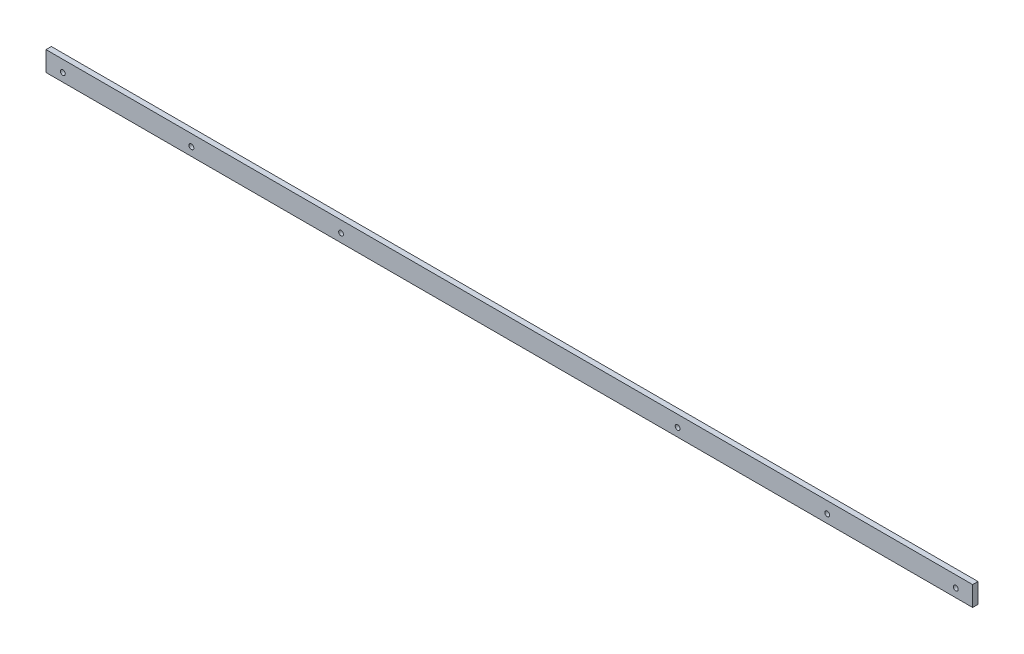
SolidWorks part; units mm, degrees
ref_plane "Front Plane" through (0, 0, 0) normal (0, 0, 1) x (1, 0, 0)
ref_plane "Top Plane" through (0, 0, 0) normal (0, 1, 0) x (1, 0, 0)
ref_plane "Right Plane" through (0, 0, 0) normal (1, 0, 0) x (0, 0, -1)
sketch "Sketch1" plane through (0, 0, 0) normal (0, 0, 1) x (1, 0, 0)
  line L1 (-275.35, 5.9) -> (275.35, 5.9)
  line L2 (-275.35, 5.9) -> (-275.35, -5.9)
  line L3 (-275.35, -5.9) -> (275.35, -5.9)
  line L4 (275.35, 5.9) -> (275.35, -5.9)
  line L5 (-275.35, 5.9) -> (275.35, -5.9) construction
  line L6 (-275.35, -5.9) -> (275.35, 5.9) construction
  point P0 (0, 0)
  dimension "D1" = 11.8
  dimension "D2" = 550.7
extrude "Boss-Extrude1" add sketch "Sketch1" along normal blind 3.18
sketch "Sketch2" plane through (0, 0, 3.18) normal (0, 0, 1) x (1, 0, 0)
  line L0 (275.35, -0.9) -> (265.35, -0.9) construction
  line L1 (275.35, -5.9) -> (275.35, 5.9) construction
  line L3 (-275.35, -5.9) -> (275.35, -5.9) construction
  circle A0 centre (265.35, -0.9) radius 1.45
  dimension "D2" = 2.9
  dimension "D3" = 5
  dimension "D1" = 10
sketch "Sketch3" plane through (0, 0, 3.18) normal (0, 0, 1) x (1, 0, 0)
  line L0 (0, -0.9) -> (100, -0.9) construction
  line L1 (-275.35, -5.9) -> (275.35, -5.9) construction
  circle A0 centre (100, -0.9) radius 1.425
  dimension "D3" = 2.85
  dimension "D1" = 100
  dimension "D2" = 5
extrude "Cut-Extrude2" cut sketch "Sketch3" against normal up to next
mirror "Mirror2" about plane through (0, 0, 0) normal (1, 0, 0) of "Cut-Extrude2"
extrude "Cut-Extrude3" cut sketch "Sketch2" against normal up to next
mirror "Mirror3" about plane through (0, 0, 0) normal (1, 0, 0) of "Cut-Extrude3"
sketch "Sketch4" plane through (0, 0, 3.18) normal (0, 0, 1) x (1, 0, 0)
  line L0 (-275.35, -0.9) -> (-188.94, -0.9) construction
  line L1 (-275.35, 5.9) -> (-275.35, -5.9) construction
  circle A0 centre (-188.94, -0.9) radius 1.45
  dimension "D2" = 2.9
  dimension "D1" = 86.41
extrude "Cut-Extrude4" cut sketch "Sketch4" against normal up to next
mirror "Mirror4" about plane through (0, 0, 0) normal (1, 0, 0) of "Cut-Extrude4"
